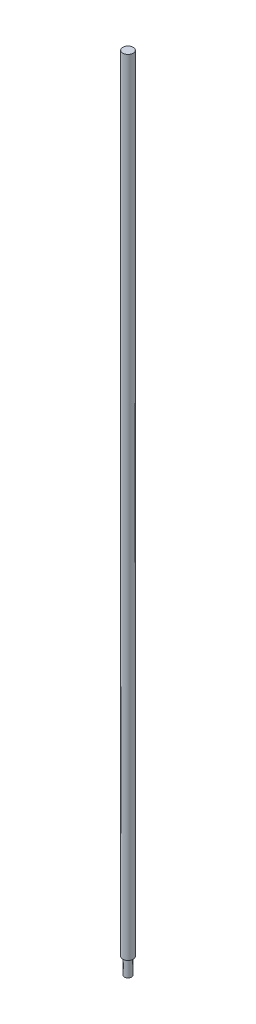
SolidWorks part; units mm, degrees
ref_plane "前视基准面" through (0, 0, 0) normal (0, 0, 1) x (1, 0, 0)
ref_plane "上视基准面" through (0, 0, 0) normal (0, 1, 0) x (1, 0, 0)
ref_plane "右视基准面" through (0, 0, 0) normal (1, 0, 0) x (0, 0, -1)
sketch "草图1" plane through (0, 0, 0) normal (0, 1, 0) x (1, 0, 0)
  circle A0 centre (0, 0) radius 3
  dimension "D1" = 6
extrude "凸台-拉伸1" add sketch "草图1" along normal blind 455
sketch "草图2" plane through (0, 0, 0) normal (0, -1, 0) x (1, 0, 0)
  circle A0 centre (0, 0) radius 2
  dimension "D1" = 4
extrude "凸台-拉伸2" add sketch "草图2" along normal blind 9.5
